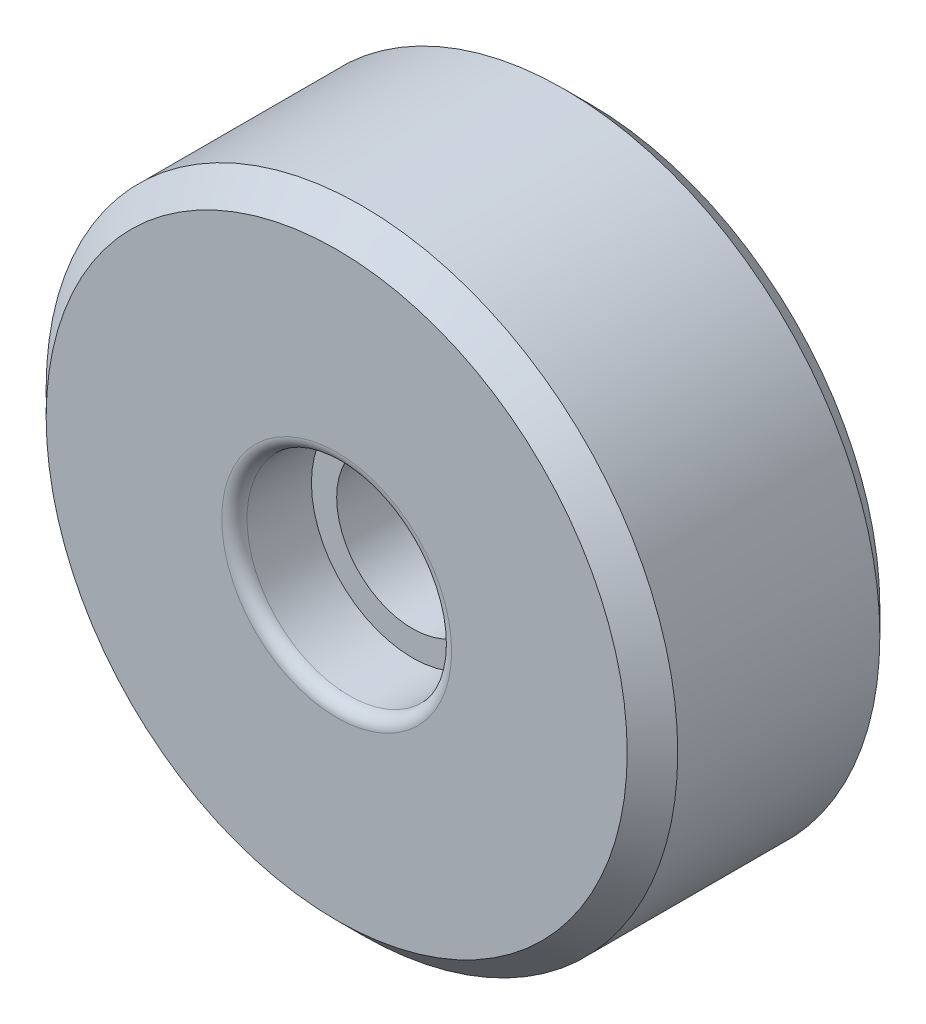
SolidWorks part; units mm, degrees
ref_plane "前视基准面" through (0, 0, 0) normal (0, 0, 1) x (1, 0, 0)
ref_plane "上视基准面" through (0, 0, 0) normal (0, 1, 0) x (1, 0, 0)
ref_plane "右视基准面" through (0, 0, 0) normal (1, 0, 0) x (0, 0, -1)
other "Configuration Table"
sketch "草图1" plane through (0, 0, 0) normal (0, 0, 1) x (1, 0, 0)
  circle A0 centre (0, 0) radius 12.5
  circle A1 centre (0, 0) radius 4.05
  dimension "D1" = 8.1
  dimension "D2" = 25
extrude "凸台-拉伸1" add sketch "草图1" along normal blind 10
sketch "草图2" plane through (0, 0, 0) normal (0, 0, -1) x (-1, 0, 0)
  circle A0 centre (0, 0) radius 4
  circle A1 centre (0, 0) radius 3
  dimension "D1" = 6
extrude "凸台-拉伸2" add sketch "草图2" against normal blind 7
chamfer "倒角1" distance 1 angle 45 2 edges at (12.5, 0, 0) (12.5, 0, 10)
fillet "圆角1" radius 0.5 1 edges at (4.05, 0, 10)
